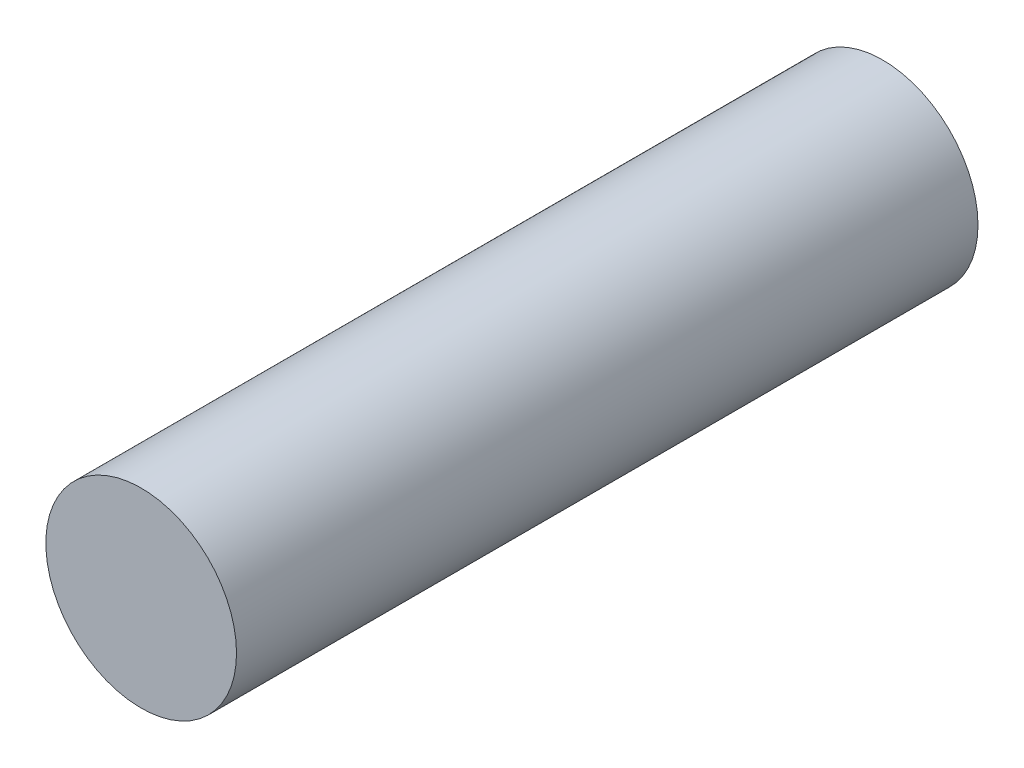
SolidWorks part; units mm, degrees
ref_plane "Front Plane" through (0, 0, 0) normal (0, 0, 1) x (1, 0, 0)
ref_plane "Top Plane" through (0, 0, 0) normal (0, 1, 0) x (1, 0, 0)
ref_plane "Right Plane" through (0, 0, 0) normal (1, 0, 0) x (0, 0, -1)
sketch "Sketch2" plane through (0, 0, 0) normal (0, 0, 1) x (1, 0, 0)
  circle A0 centre (0, 0) radius 9
  dimension "D1" = 18
extrude "Boss-Extrude1" add sketch "Sketch2" along normal blind 70
